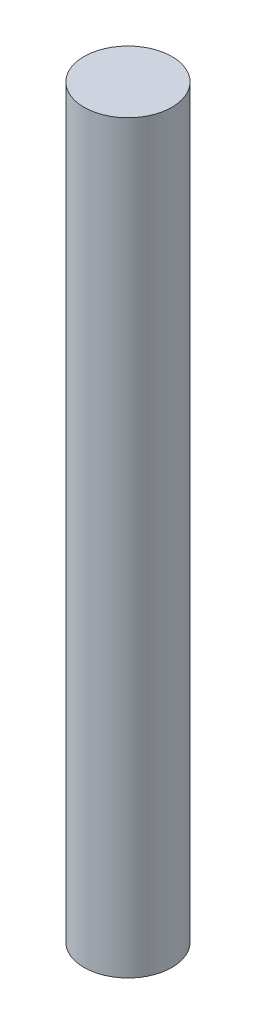
SolidWorks part; units mm, degrees
ref_plane "Front Plane" through (0, 0, 0) normal (0, 0, 1) x (1, 0, 0)
ref_plane "Top Plane" through (0, 0, 0) normal (0, 1, 0) x (1, 0, 0)
ref_plane "Right Plane" through (0, 0, 0) normal (1, 0, 0) x (0, 0, -1)
sketch "Sketch1" plane through (0, 0, 0) normal (0, 1, 0) x (1, 0, 0)
  circle A0 centre (0, 0) radius 7.375
  dimension "D1" = 14.75
extrude "Boss-Extrude1" add sketch "Sketch1" along normal blind 125
